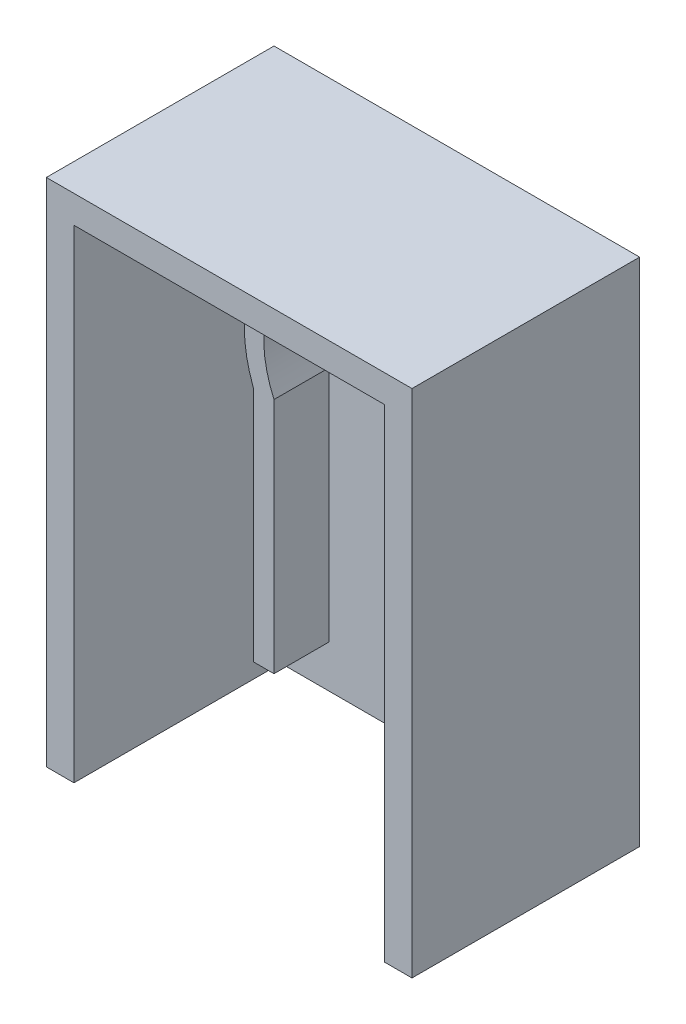
SolidWorks part; units mm, degrees
ref_plane "Front Plane" through (0, 0, 0) normal (0, 0, 1) x (1, 0, 0)
ref_plane "Top Plane" through (0, 0, 0) normal (0, 1, 0) x (1, 0, 0)
ref_plane "Right Plane" through (0, 0, 0) normal (1, 0, 0) x (0, 0, -1)
sketch "Sketch1" plane through (0, 0, 0) normal (0, 0, 1) x (1, 0, 0)
  line L0 (-7.75, -19.2024) -> (-7.75, -3.4911)
  line L2 (7.75, -19.2024) -> (7.75, -3.4911)
  line L3 (-9.25, -3.4911) -> (-9.25, -20.7024)
  line L9 (9.25, -20.7024) -> (9.25, -3.4911)
  line L10 (9.25, -20.7024) -> (7.75, -20.7024)
  line L11 (7.75, -20.7024) -> (7.75, -19.2024)
  line L12 (-7.75, -19.2024) -> (-7.75, -20.7024)
  line L13 (-7.75, -20.7024) -> (-9.25, -20.7024)
  arc A1 (-7.75, -3.4911) -> (7.75, -3.4911) centre (0, 0) cw
  arc A3 (9.25, -3.4911) -> (-9.25, -3.4911) centre (0, 0.0552) ccw
  dimension "D1" = 1.5
  dimension "D3" = 8.5
  dimension "D6" = 0
  dimension "D2" = 1.5
  dimension "D5" = 0
extrude "Boss-Extrude1" add sketch "Sketch1" along normal blind 4
sketch "Sketch3" plane through (0, 0, 0) normal (0, 0, 1) x (1, 0, 0)
  line L1 (-11.25, 11.2) -> (11.25, 11.2)
  line L2 (-11.25, 11.2) -> (-11.25, -23.8)
  line L3 (-11.25, -23.8) -> (11.25, -23.8)
  line L4 (11.25, 11.2) -> (11.25, -23.8)
  arc A0 (7.75, -3.4911) -> (-7.75, -3.4911) centre (0, 0) ccw construction
  point P0 (0, 0)
  point P6 (0, 11.2)
  point P10 (0, 8.5)
  dimension "D1" = 2.7
  dimension "D2" = 11.25
  dimension "D3" = 11.25
  dimension "D4" = 35
extrude "Boss-Extrude2" add sketch "Sketch3" against normal blind 1.5
sketch "Sketch9" plane through (0, 0, 0) normal (0, 0, 1) x (1, 0, 0)
  line L1 (-13.25, 13.2) -> (13.25, 13.2)
  line L5 (-11.25, 11.2) -> (11.25, 11.2)
  line L8 (11.25, 11.2) -> (11.25, -23.8)
  line L15 (-13.25, 13.2) -> (-13.25, -23.8)
  line L16 (-13.25, -23.8) -> (-11.25, -23.8)
  line L17 (-11.25, -23.8) -> (-11.25, 11.2)
  line L18 (13.25, 13.2) -> (13.25, -23.8)
  line L19 (13.25, -23.8) -> (11.25, -23.8)
  dimension "D3" = 2
extrude "Boss-Extrude5" add sketch "Sketch9" along normal blind 15 separate body
sketch "Sketch10" plane through (0, 0, 0) normal (0, 0, 1) x (1, 0, 0)
  line L1 (-13.25, 13.2) -> (13.25, 13.2)
  line L5 (11.25, 11.2) -> (-11.25, 11.2)
  line L8 (-13.25, -23.8) -> (-13.25, 13.2)
  line L9 (-11.25, 11.2) -> (-11.25, -23.8)
  line L10 (-11.25, -23.8) -> (-13.25, -23.8)
  line L11 (11.25, -23.8) -> (11.25, 11.2)
  line L12 (13.25, 13.2) -> (13.25, -23.8)
  line L13 (13.25, -23.8) -> (11.25, -23.8)
extrude "Boss-Extrude6" add sketch "Sketch10" against normal blind 1.5
